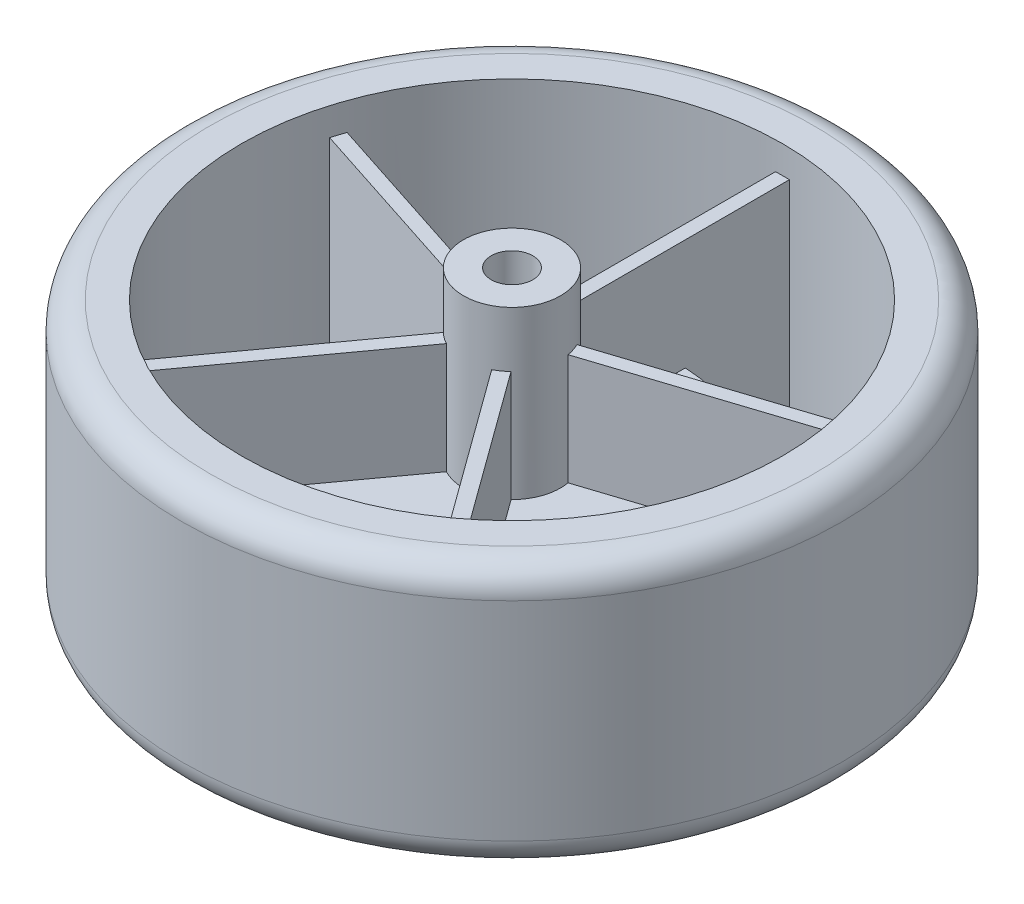
SolidWorks part; units mm, degrees
ref_plane "前视基准面" through (0, 0, 0) normal (0, 0, 1) x (1, 0, 0)
ref_plane "上视基准面" through (0, 0, 0) normal (0, 1, 0) x (1, 0, 0)
ref_plane "右视基准面" through (0, 0, 0) normal (1, 0, 0) x (0, 0, -1)
sketch "草图1" plane through (0, 0, 0) normal (0, 0, 1) x (1, 0, 0)
  line L0 (0, 0) -> (0, -43.7247) construction
  line L1 (19.5, 9.5) -> (19.5, -7.5)
  line L2 (19.5, -7.5) -> (0, -7.5)
  line L3 (0, -7.5) -> (0, -9.5)
  line L5 (23.75, 7.5) -> (23.75, -7.5)
  line L6 (19.5, 9.5) -> (21.75, 9.5)
  line L8 (0, -9.5) -> (21.75, -9.5)
  line L10 (23.75, 0) -> (0, 0) construction
  arc A0 (21.75, -9.5) -> (23.75, -7.5) centre (21.75, -7.5) ccw
  arc A1 (23.75, 7.5) -> (21.75, 9.5) centre (21.75, 7.5) ccw
  dimension "D7" = 2
  dimension "D1" = 19
  dimension "D2" = 47.5
  dimension "D3" = 39
  dimension "D4" = 2
revolve "旋转1" add sketch "草图1" angle 360 about L0
sketch "草图2" plane through (0, -7.5, 0) normal (0, 1, 0) x (1, 0, 0)
  circle A0 centre (0, 0) radius 5
  dimension "D1" = 10
extrude "凸台-拉伸1" add sketch "草图2" along normal blind 5
sketch "草图3" plane through (0, -2.5, 0) normal (0, 1, 0) x (1, 0, 0)
  circle A0 centre (0, 0) radius 12
  dimension "D1" = 24
extrude "凸台-拉伸2" add sketch "草图3" along normal blind 2
sketch "草图5" plane through (0, -0.5, 0) normal (0, 1, 0) x (1, 0, 0)
  circle A0 centre (0, 0) radius 1.5
  circle A1 centre (0, 0) radius 3.5
  dimension "D1" = 3
  dimension "D2" = 7
extrude "凸台-拉伸3" add sketch "草图5" along normal blind 12
sketch "草图6" plane through (0, -7.5, 0) normal (0, 1, 0) x (1, 0, 0)
  line L0 (0, 23.75) -> (0, -23.75) construction
  line L1 (-0.5, 19.4936) -> (-0.5, 3.4641)
  line L2 (0.5, 19.4936) -> (0.5, 3.4641)
  circle A0 centre (0, 0) radius 23.75 construction
  circle A1 centre (0, 0) radius 19.5 construction
  circle A2 centre (0, 0) radius 3.5 construction
  arc A3 (0.5, 19.4936) -> (-0.5, 19.4936) centre (0, 0) ccw
  arc A4 (0.5, 3.4641) -> (-0.5, 3.4641) centre (0, 0) ccw
  dimension "D1" = 1
  dimension "D2" = 1
extrude "凸台-拉伸4" add sketch "草图6" along normal blind 15
pattern_circular "阵列(圆周)1" count 5 over 360 about axis through (0, 0, 0) along (0, 1, 0) of "凸台-拉伸4"
sketch "草图7" plane through (0, -7.5, 0) normal (0, 1, 0) x (1, 0, 0)
  line L0 (1.2543, 11.9343) -> (1.5679, 14.9178)
  line L1 (10.9625, 4.8808) -> (13.7032, 6.101)
  line L2 (0, 0) -> (18.5456, 6.0258) construction
  line L3 (0, 0) -> (0, 19.5) construction
  line L4 (0, 0) -> (8.8168, 12.1353) construction
  arc A1 (13.7032, 6.101) -> (1.5679, 14.9178) centre (0, 0) ccw
  arc A2 (18.694, 5.5483) -> (18.385, 6.4994) centre (0, 0) ccw construction
  arc A3 (0.5, 19.4936) -> (-0.5, 19.4936) centre (0, 0) ccw construction
  arc A4 (11.2483, 4.1805) -> (0.5, 11.9896) centre (0, 0) ccw construction
  arc A5 (10.9625, 4.8808) -> (1.2543, 11.9343) centre (0, 0) ccw
  point P3 (0, 0)
  dimension "D2" = 30
  dimension "D3" = 60
  dimension "D4" = 12
  dimension "D1" = 36
extrude "切除-拉伸1" cut sketch "草图7" against normal blind 15
pattern_circular "阵列(圆周)2" count 5 over 360 about axis through (0, 0, 0) along (0, 1, 0) of "切除-拉伸1"
